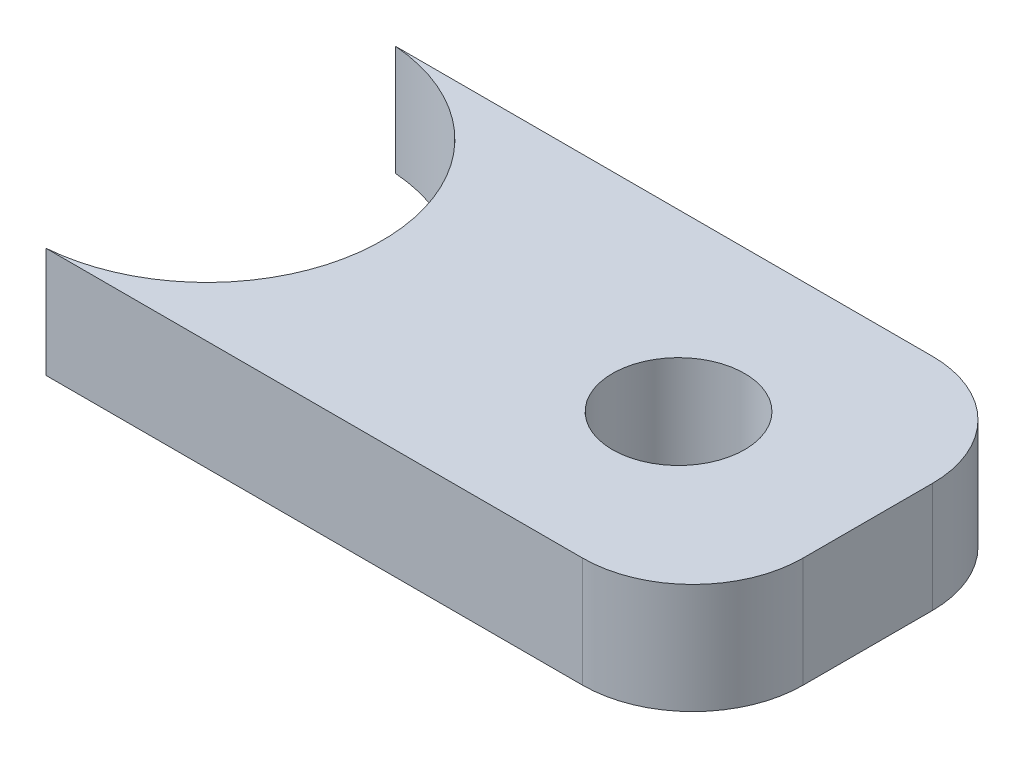
SolidWorks part; units mm, degrees
ref_plane "Front Plane" through (0, 0, 0) normal (0, 0, 1) x (1, 0, 0)
ref_plane "Top Plane" through (0, 0, 0) normal (0, 1, 0) x (1, 0, 0)
ref_plane "Right Plane" through (0, 0, 0) normal (1, 0, 0) x (0, 0, -1)
sketch "Sketch1" plane through (0, 0, 0) normal (0, 1, 0) x (1, 0, 0)
  line L1 (-1.1811, 0.625) -> (0.7874, 0.625)
  line L2 (-1.1811, 0.625) -> (-1.1811, -0.625)
  line L3 (-1.1811, -0.625) -> (0.7874, -0.625)
  line L4 (1.1811, 0.2313) -> (1.1811, -0.2313)
  line L5 (-1.1811, 0.625) -> (1.1811, -0.625) construction
  line L6 (-1.1811, -0.625) -> (1.1811, 0.625) construction
  circle A0 centre (-1.1811, 0) radius 0.627
  circle A1 centre (0.505, 0) radius 0.2362
  arc A2 (0.7874, -0.625) -> (1.1811, -0.2313) centre (0.7874, -0.2313) ccw
  arc A3 (0.7874, 0.625) -> (1.1811, 0.2313) centre (0.7874, 0.2313) cw
  point P0 (0, 0)
  dimension "D3" = 0.4724
  dimension "D4" = 0.3937
  dimension "D1" = 2.3622
  dimension "D2" = 1.25
extrude "Boss-Extrude1" add sketch "Sketch1" along normal blind 0.3937 contours A3 L1 A0 L3 A2 L4 A1
